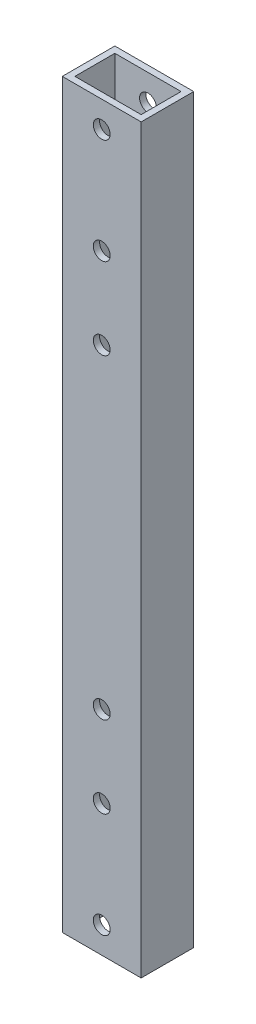
SolidWorks part; units mm, degrees
ref_plane "正面" through (0, 0, 0) normal (0, 0, 1) x (1, 0, 0)
ref_plane "平面" through (0, 0, 0) normal (0, 1, 0) x (1, 0, 0)
ref_plane "右側面" through (0, 0, 0) normal (1, 0, 0) x (0, 0, -1)
sketch "ｽｹｯﾁ1" plane through (0, 0, 0) normal (0, 1, 0) x (1, 0, 0)
  line L0 (-6.3, 3.8) -> (6.3, 3.8)
  line L1 (-7.5, 5) -> (7.5, 5)
  line L2 (-7.5, 5) -> (-7.5, -5)
  line L3 (-7.5, -5) -> (7.5, -5)
  line L4 (7.5, 5) -> (7.5, -5)
  line L5 (-7.5, 5) -> (7.5, -5) construction
  line L6 (-7.5, -5) -> (7.5, 5) construction
  line L7 (6.3, 3.8) -> (6.3, -3.8)
  line L8 (-6.3, -3.8) -> (6.3, -3.8)
  line L9 (-6.3, 3.8) -> (-6.3, -3.8)
  point P0 (0, 0)
  dimension "D1" = 15
  dimension "D2" = 10
  dimension "D3" = 1.2
extrude "ﾎﾞｽ - 押し出し1" add sketch "ｽｹｯﾁ1" along normal mid plane 141
sketch "ｽｹｯﾁ2" plane through (0, 0, -5) normal (0, 0, -1) x (-1, 0, 0)
  line L0 (0, 0) -> (-7.5, 0) construction
  line L1 (-7.5, 70.5) -> (-7.5, -70.5) construction
  line L2 (0, 0) -> (0, -70.5) construction
  line L3 (-7.5, -70.5) -> (7.5, -70.5) construction
  circle A0 centre (0, -65.5) radius 1.6
  circle A1 centre (0, -45.5) radius 1.6
  circle A2 centre (0, 45.5) radius 1.6
  circle A3 centre (0, 65.5) radius 1.6
  dimension "D1" = 3.2
  dimension "D2" = 3.2
  dimension "D3" = 5
  dimension "D4" = 20
extrude "ｶｯﾄ - 押し出し1" cut sketch "ｽｹｯﾁ2" against normal blind 100
sketch "ｽｹｯﾁ3" plane through (0, 0, -5) normal (0, 0, -1) x (-1, 0, 0)
  circle A0 centre (0, -30) radius 1.6 construction
  circle A1 centre (0, 30) radius 1.6 construction
  circle A2 centre (0, -30) radius 1.6
  circle A3 centre (0, 30) radius 1.6
extrude "ｶｯﾄ - 押し出し2" cut sketch "ｽｹｯﾁ3" against normal blind 10
